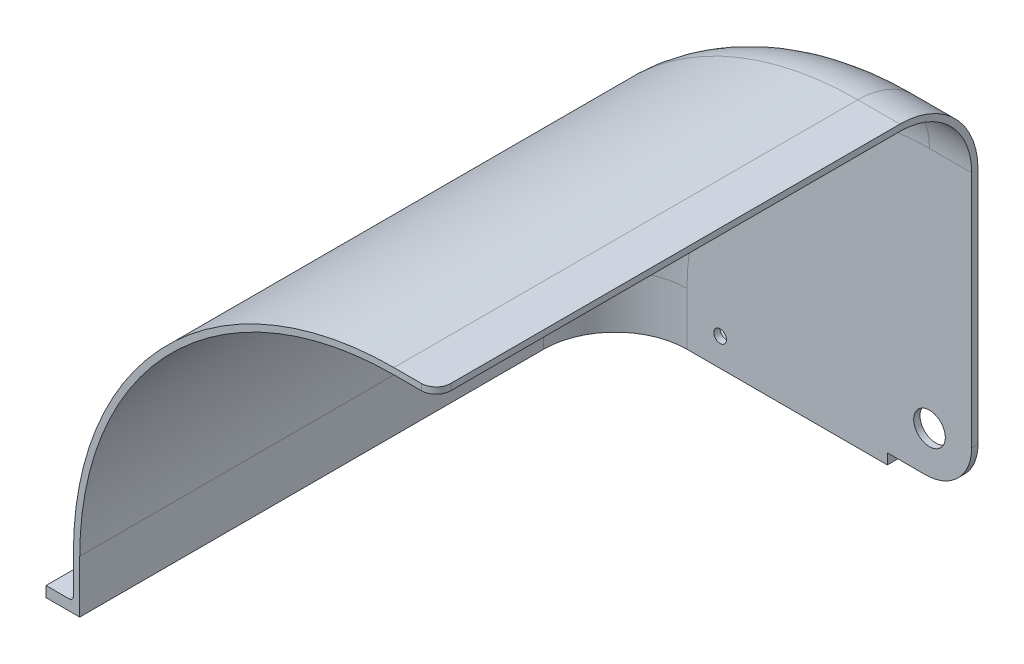
SolidWorks part; units mm, degrees
ref_plane "Front Plane" through (0, 0, 0) normal (0, 0, 1) x (1, 0, 0)
ref_plane "Top Plane" through (0, 0, 0) normal (0, 1, 0) x (1, 0, 0)
ref_plane "Right Plane" through (0, 0, 0) normal (1, 0, 0) x (0, 0, -1)
sketch "Sketch1" plane through (0, 0, 0) normal (0, 1, 0) x (1, 0, 0)
  line L0 (0, -254) -> (0, 254) construction
  line L2 (-165, 270) -> (-165, -270)
  line L5 (-165, 270) -> (0, 0) construction
  line L6 (-165, -270) -> (0, 0) construction
  line L9 (-149, -254) -> (-149, 254)
  line L11 (-149, 254) -> (0, 254)
  line L12 (-165, 270) -> (0, 270)
  line L21 (-149, -254) -> (0, -254)
  line L22 (-165, -270) -> (0, -270)
  line L23 (0, 254) -> (0, 270)
  line L24 (0, -254) -> (0, -270)
  line L25 (0, 270) -> (0, 264) construction
  line L26 (0, 264) -> (-40, 264) construction
  line L27 (-40, 264) -> (-120, 264) construction
  line L28 (-165, 0) -> (-159, 0) construction
  line L29 (-159, 0) -> (-159, 50) construction
  line L30 (-159, 50) -> (-159, 130) construction
  line L31 (0, 0) -> (-149, 0) construction
  line L32 (-159, 210) -> (-159, 50) construction
  line L33 (-40, -264) -> (-120, -264) construction
  line L34 (-159, -210) -> (-159, -50) construction
  line L35 (-159, -50) -> (-159, -130) construction
  circle A0 centre (-159, 130) radius 1.6
  circle A1 centre (-159, 50) radius 1.6
  circle A2 centre (-120, 264) radius 1.6
  circle A3 centre (-40, 264) radius 1.6
  circle A4 centre (-159, 210) radius 1.6
  circle A5 centre (-40, -264) radius 1.6
  circle A6 centre (-120, -264) radius 1.6
  circle A7 centre (-159, -210) radius 1.6
  circle A8 centre (-159, -50) radius 1.6
  circle A9 centre (-159, -130) radius 1.6
  point P0 (0, 0)
  point P9 (0, 0)
  point P26 (-159, 130)
  point P38 (-159, -130)
  dimension "D13" = 80
  dimension "D1" = 16
  dimension "D2" = 540
  dimension "D3" = 16
  dimension "D4" = 16
  dimension "D5" = 165
  dimension "D6" = 165
  dimension "D7" = 6
  dimension "D8" = 80
  dimension "D9" = 40
  dimension "D10" = 6
  dimension "D11" = 50
  dimension "D12" = 80
extrude "Boss-Extrude1" add sketch "Sketch1" along normal blind 5
sketch "Sketch12" plane through (0, 5, 0) normal (0, 1, 0) x (1, 0, 0)
  line L0 (0, -254) -> (-149, -254) construction
  line L1 (0, 254) -> (-149, 254)
  line L2 (0, 254) -> (0, -254) construction
  line L3 (0, -254) -> (-149, -254)
  line L4 (-149, 254) -> (-149, -254)
  line L5 (0, 257) -> (-152, 257)
  line L6 (-152, 257) -> (-152, -257)
  line L7 (0, -257) -> (-152, -257)
  line L8 (0, 257) -> (0, 254)
  line L9 (0, -257) -> (0, -254)
  dimension "D1" = 3
extrude "Boss-Extrude5" add sketch "Sketch12" along normal blind 20
fillet "Fillet8" radius 34 2 edges at (-149, 12.5, 254) (-149, 12.5, -254)
fillet "Fillet9" radius 37 2 edges at (-152, 15, -257) (-152, 15, 257)
sketch "Sketch13" plane through (0, 25, 0) normal (0, 1, 0) x (1, 0, 0)
  line L0 (0, 254) -> (-115, 254)
  line L1 (0, 257) -> (-115, 257)
  line L2 (0, 257) -> (0, -257) construction
  line L3 (0, -257) -> (-115, -257)
  line L4 (-152, 220) -> (-152, -220)
  line L5 (-149, 220) -> (-149, -220)
  line L6 (0, -254) -> (-115, -254)
  line L7 (0, 257) -> (0, 254)
  line L8 (0, -257) -> (0, -254)
  arc A0 (-115, 257) -> (-152, 220) centre (-115, 220) ccw
  arc A1 (-115, -257) -> (-152, -220) centre (-115, -220) cw
  arc A2 (-115, 254) -> (-149, 220) centre (-115, 220) ccw
  arc A3 (-115, -254) -> (-149, -220) centre (-115, -220) cw
  dimension "D3" = 37
  dimension "D4" = 37
  dimension "D1" = 152
  dimension "D2" = 514
  dimension "D5" = 3
revolve "Revolve4" add sketch "Sketch13" angle 90 about L2
sketch "Sketch15" plane through (0, 0, 0) normal (1, 0, 0) x (0, 0, -1)
  line L0 (-254, 5) -> (-254, 140)
  line L1 (-257, 5) -> (257, 5) construction
  line L2 (-257, 5) -> (-257, 140)
  line L3 (-220, 177) -> (220, 177)
  line L4 (257, 5) -> (257, 140)
  line L5 (-220, 174) -> (220, 174)
  line L6 (254, 5) -> (254, 140)
  line L7 (-257, 5) -> (-270, 5)
  line L8 (-270, 5) -> (-270, 0)
  line L9 (-270, 0) -> (-254, 0)
  line L10 (-254, 0) -> (-254, 5)
  line L11 (254, 5) -> (254, 0)
  line L12 (254, 0) -> (270, 0)
  line L13 (270, 0) -> (270, 5)
  line L14 (270, 5) -> (257, 5)
  arc A0 (-220, 177) -> (-257, 140) centre (-220, 140) ccw
  arc A1 (257, 140) -> (220, 177) centre (220, 140) ccw
  arc A2 (-220, 174) -> (-254, 140) centre (-220, 140) ccw
  arc A3 (254, 140) -> (220, 174) centre (220, 140) ccw
  dimension "D3" = 37
  dimension "D4" = 37
  dimension "D1" = 514
  dimension "D2" = 172
  dimension "D5" = 3
extrude "Boss-Extrude6" add sketch "Sketch15" along normal blind 20
sketch "Sketch16" plane through (0, 0, 270) normal (0, 0, 1) x (1, 0, 0)
  line L0 (-115, 5) -> (20, 5) construction
  line L1 (20, 0) -> (-20, 0)
  line L2 (20, 0) -> (20, 5)
  line L3 (20, 5) -> (-20, 5)
  line L4 (-20, 0) -> (-20, 5)
  dimension "D1" = 40
  dimension "D2" = 5
extrude "Cut-Extrude3" cut sketch "Sketch16" against normal up to surface (540 mm away) up to face at (-72.5, 2.5, -270)
fillet "Fillet10" radius 22 2 edges at (20, 5, 255.5) (20, 5, -255.5)
sketch "Sketch17" plane through (0, 0, 257) normal (0, 0, 1) x (1, 0, 0)
  line L0 (-115, 25) -> (20, 25) construction
  line L1 (20, 140) -> (20, 27) construction
  line L2 (0, 140) -> (0, 0) construction
  arc A0 (0, 140) -> (-115, 25) centre (0, 25) ccw construction
  circle A1 centre (0, 25) radius 7.5
  dimension "D1" = 25
extrude "Cut-Extrude4" cut sketch "Sketch17" against normal up to surface (514 mm away) up to face at (-33.0373, 52.323, -257)
fillet "Fillet11" radius 5 2 edges at (-165, 2.5, -270) (-165, 2.5, 270)
fillet "Fillet12" radius 2 5 edges at (-67.5, 5, -257) (-141.163, 5, -246.163) (-67.5, 5, 257) (-141.163, 5, 246.163) (-152, 5, 0)
sketch "Sketch18" plane through (0, 0, -257) normal (0, 0, -1) x (-1, 0, 0)
  line L0 (0, 25) -> (152, 7) construction
  line L1 (152, 25) -> (152, 7) construction
  line L2 (115, 7) -> (152, 7) construction
  line L3 (0, 25) -> (99.3061, 13.2401) construction
  circle A0 centre (99.3061, 13.2401) radius 3
  dimension "D2" = 6
  dimension "D1" = 100
extrude "Cut-Extrude5" cut sketch "Sketch18" against normal up to surface (7 mm away)
sketch "Sketch19" plane through (0, 0, 0) normal (0, -1, 0) x (1, 0, 0)
  line L0 (0, 0) -> (20, 0) construction
  line L1 (0, 220) -> (0, -220) construction
  line L2 (20, 220) -> (20, -220) construction
  line L4 (20, 0) -> (-221.3994, 0)
  line L5 (20, 0) -> (20, 285.511)
  line L6 (20, 285.511) -> (-221.3994, 285.511)
  line L7 (-221.3994, 0) -> (-221.3994, 285.511)
  point P9 (-221.3994, 285.511)
extrude "Cut-Extrude6" cut sketch "Sketch19" against normal blind 269
fillet "Fillet13" radius 7 1 edges at (20, 175.5, 0)
